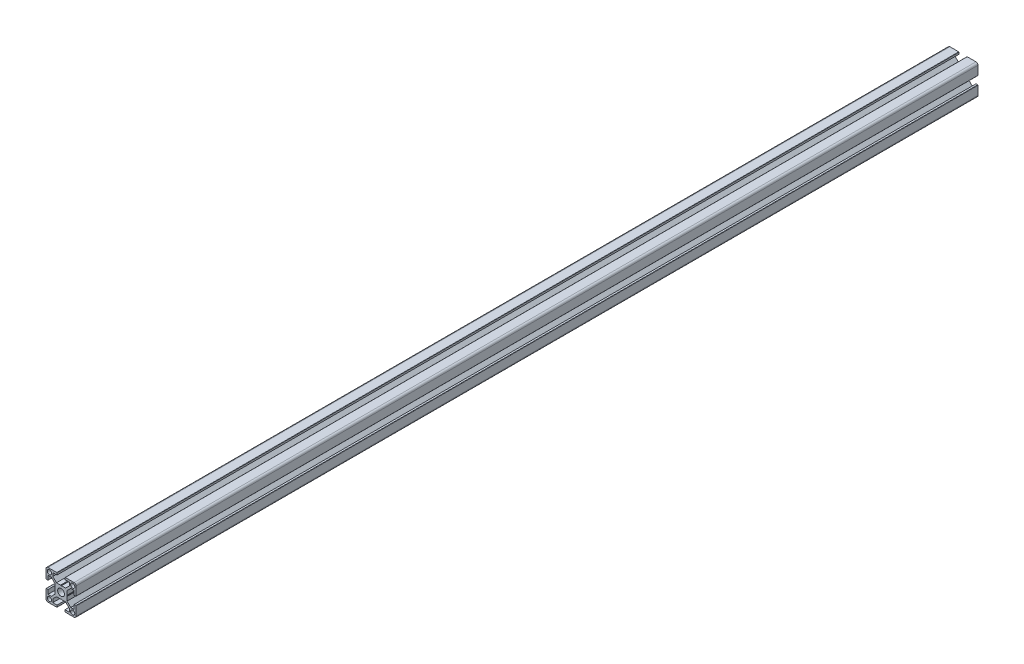
SolidWorks part; units mm, degrees
ref_plane "Front Plane" through (0, 0, 0) normal (0, 0, 1) x (1, 0, 0)
ref_plane "Top Plane" through (0, 0, 0) normal (0, 1, 0) x (1, 0, 0)
ref_plane "Right Plane" through (0, 0, 0) normal (1, 0, 0) x (0, 0, -1)
ref_plane "Plane1" through (0, 0, 0) normal (0, 0, 1) x (1, 0, 0)
sketch "Sketch1" plane through (0, 0, 0) normal (0, 0, 1) x (1, 0, 0)
  line L0 (-15, -4.3) -> (-15, -13)
  line L1 (-13, -15) -> (-4.3, -15)
  line L2 (-4, -14.7) -> (-4, -13)
  line L3 (-4, -13) -> (-8.25, -13)
  line L4 (-8.25, -13) -> (-8.25, -9.6642)
  line L5 (-8.25, -9.6642) -> (-4.5858, -6)
  line L6 (-4.5858, -6) -> (-0.5196, -6)
  line L7 (-0.5196, -6) -> (0, -5.7)
  line L8 (0, -5.7) -> (0.5196, -6)
  line L9 (0.5196, -6) -> (4.5858, -6)
  line L10 (4.5858, -6) -> (8.25, -9.6642)
  line L11 (8.25, -9.6642) -> (8.25, -13)
  line L12 (8.25, -13) -> (4, -13)
  line L13 (4, -13) -> (4, -14.7)
  line L14 (4.3, -15) -> (13, -15)
  line L15 (15, -13) -> (15, -4.3)
  line L16 (14.7, -4) -> (13, -4)
  line L17 (13, -4) -> (13, -8.25)
  line L18 (13, -8.25) -> (9.6642, -8.25)
  line L19 (9.6642, -8.25) -> (6, -4.5858)
  line L20 (6, -4.5858) -> (6, -0.5196)
  line L21 (6, -0.5196) -> (5.7, 0)
  line L22 (5.7, 0) -> (6, 0.5196)
  line L23 (6, 0.5196) -> (6, 4.5858)
  line L24 (6, 4.5858) -> (9.6642, 8.25)
  line L25 (9.6642, 8.25) -> (13, 8.25)
  line L26 (13, 8.25) -> (13, 4)
  line L27 (13, 4) -> (14.7, 4)
  line L28 (15, 4.3) -> (15, 13)
  line L29 (13, 15) -> (4.3, 15)
  line L30 (4, 14.7) -> (4, 13)
  line L31 (4, 13) -> (8.25, 13)
  line L32 (8.25, 13) -> (8.25, 9.6642)
  line L33 (8.25, 9.6642) -> (4.5858, 6)
  line L34 (4.5858, 6) -> (0.5196, 6)
  line L35 (0.5196, 6) -> (0, 5.7)
  line L36 (0, 5.7) -> (-0.5196, 6)
  line L37 (-0.5196, 6) -> (-4.5858, 6)
  line L38 (-4.5858, 6) -> (-8.25, 9.6642)
  line L39 (-8.25, 9.6642) -> (-8.25, 13)
  line L40 (-8.25, 13) -> (-4, 13)
  line L41 (-4, 13) -> (-4, 14.7)
  line L42 (-4.3, 15) -> (-13, 15)
  line L43 (-15, 13) -> (-15, 4.3)
  line L44 (-14.7, 4) -> (-13, 4)
  line L45 (-13, 4) -> (-13, 8.25)
  line L46 (-13, 8.25) -> (-9.6642, 8.25)
  line L47 (-9.6642, 8.25) -> (-6, 4.5858)
  line L48 (-6, 4.5858) -> (-6, 0.5196)
  line L49 (-6, 0.5196) -> (-5.7, 0)
  line L50 (-5.7, 0) -> (-6, -0.5196)
  line L51 (-6, -0.5196) -> (-6, -4.5858)
  line L52 (-6, -4.5858) -> (-9.6642, -8.25)
  line L53 (-9.6642, -8.25) -> (-13, -8.25)
  line L54 (-13, -8.25) -> (-13, -4)
  line L55 (-13, -4) -> (-14.7, -4)
  arc A0 (-15, -13) -> (-13, -15) centre (-13, -13) ccw
  arc A1 (-4.3, -15) -> (-4, -14.7) centre (-4.3, -14.7) ccw
  arc A2 (4, -14.7) -> (4.3, -15) centre (4.3, -14.7) ccw
  arc A3 (13, -15) -> (15, -13) centre (13, -13) ccw
  arc A4 (15, -4.3) -> (14.7, -4) centre (14.7, -4.3) ccw
  arc A5 (14.7, 4) -> (15, 4.3) centre (14.7, 4.3) ccw
  arc A6 (15, 13) -> (13, 15) centre (13, 13) ccw
  arc A7 (4.3, 15) -> (4, 14.7) centre (4.3, 14.7) ccw
  arc A8 (-4, 14.7) -> (-4.3, 15) centre (-4.3, 14.7) ccw
  arc A9 (-13, 15) -> (-15, 13) centre (-13, 13) ccw
  arc A10 (-15, 4.3) -> (-14.7, 4) centre (-14.7, 4.3) ccw
  arc A11 (-14.7, -4) -> (-15, -4.3) centre (-14.7, -4.3) ccw
  circle A12 centre (11.625, -11.625) radius 2.1
  circle A13 centre (11.625, 11.625) radius 2.1
  circle A14 centre (0, 0) radius 3.4
  circle A15 centre (-11.625, -11.625) radius 2.1
  circle A16 centre (-11.625, 11.625) radius 2.1
extrude "Boss-Extrude1" add sketch "Sketch1" against normal blind 900
